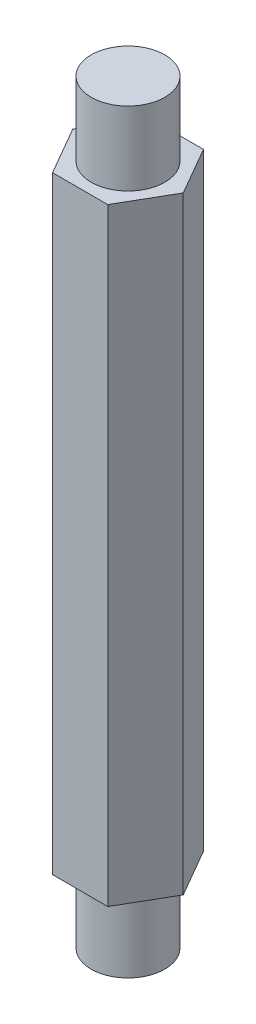
SolidWorks part; units mm, degrees
ref_plane "前视基准面" through (0, 0, 0) normal (0, 0, 1) x (1, 0, 0)
ref_plane "上视基准面" through (0, 0, 0) normal (0, 1, 0) x (1, 0, 0)
ref_plane "右视基准面" through (0, 0, 0) normal (1, 0, 0) x (0, 0, -1)
sketch "草图1" plane through (0, 0, 0) normal (0, 1, 0) x (1, 0, 0)
  circle A0 centre (0, 0) radius 1
  dimension "D1" = 2
extrude "凸台-拉伸1" add sketch "草图1" along normal blind 2
sketch "草图2" plane through (0, 2, 0) normal (0, 1, 0) x (1, 0, 0)
  line L1 (1.5011, 0) -> (0.7506, 1.3)
  line L2 (0.7506, 1.3) -> (-0.7506, 1.3)
  line L3 (-0.7506, 1.3) -> (-1.5011, 0)
  line L4 (-1.5011, 0) -> (-0.7506, -1.3)
  line L5 (-0.7506, -1.3) -> (0.7506, -1.3)
  line L6 (0.7506, -1.3) -> (1.5011, 0)
  circle A0 centre (0, 0) radius 1.3 construction
  dimension "D1" = 2.6
extrude "凸台-拉伸2" add sketch "草图2" along normal blind 16.52
sketch "草图3" plane through (0, 18.52, 0) normal (0, 1, 0) x (1, 0, 0)
  circle A0 centre (0, 0) radius 1
  dimension "D1" = 2
extrude "凸台-拉伸3" add sketch "草图3" along normal blind 2
